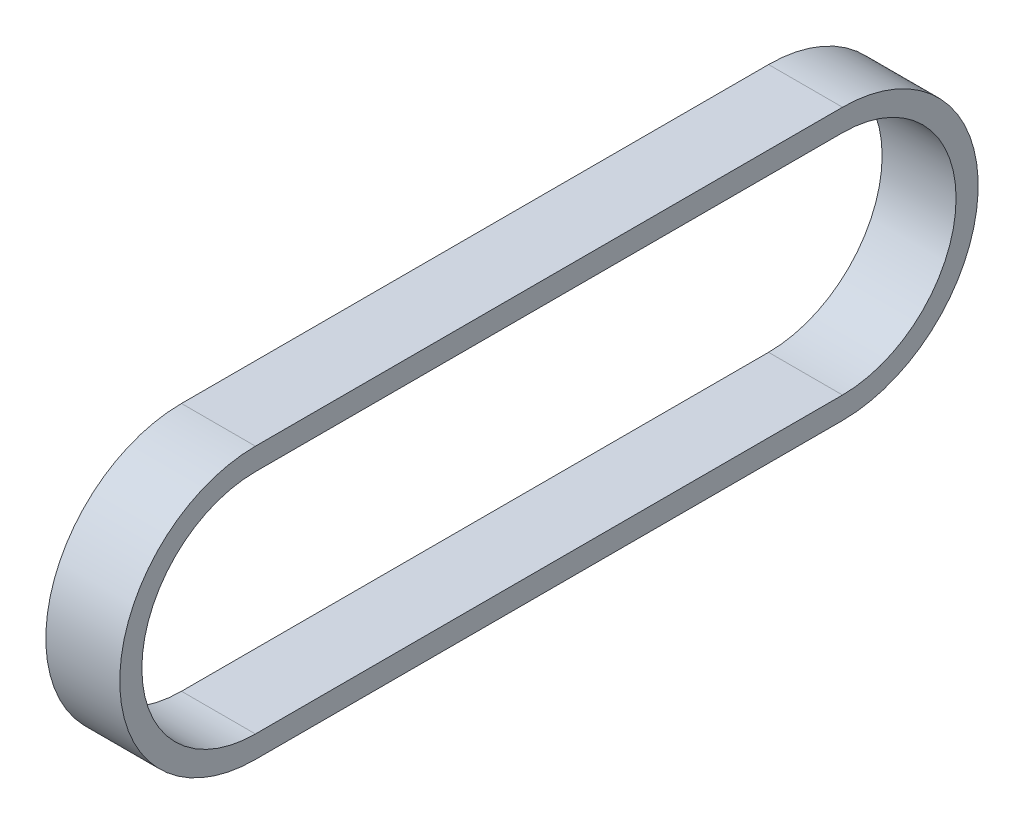
SolidWorks part; units mm, degrees
ref_plane "Front" through (0, 0, 0) normal (0, 0, 1) x (1, 0, 0)
ref_plane "Top" through (0, 0, 0) normal (0, 1, 0) x (1, 0, 0)
ref_plane "Right" through (0, 0, 0) normal (1, 0, 0) x (0, 0, -1)
sketch "Sketch1" plane through (0, 0, 0) normal (1, 0, 0) x (0, 0, -1)
  line L0 (-33.7439, 0) -> (33.7439, 0) construction
  line L1 (-33.7439, 14.3256) -> (33.7439, 14.3256)
  line L2 (-33.7439, -14.3256) -> (33.7439, -14.3256)
  arc A0 (-33.7439, 14.3256) -> (-33.7439, -14.3256) centre (-33.7439, 0) ccw
  arc A1 (33.7439, -14.3256) -> (33.7439, 14.3256) centre (33.7439, 0) ccw
  point P2 (0, 0)
  dimension "D2" = 28.6512
  dimension "D1" = 67.4878
extrude "Extrude-Thin1" add sketch "Sketch1" along normal blind 8.5 thin thin type mid plane wall 2.54
